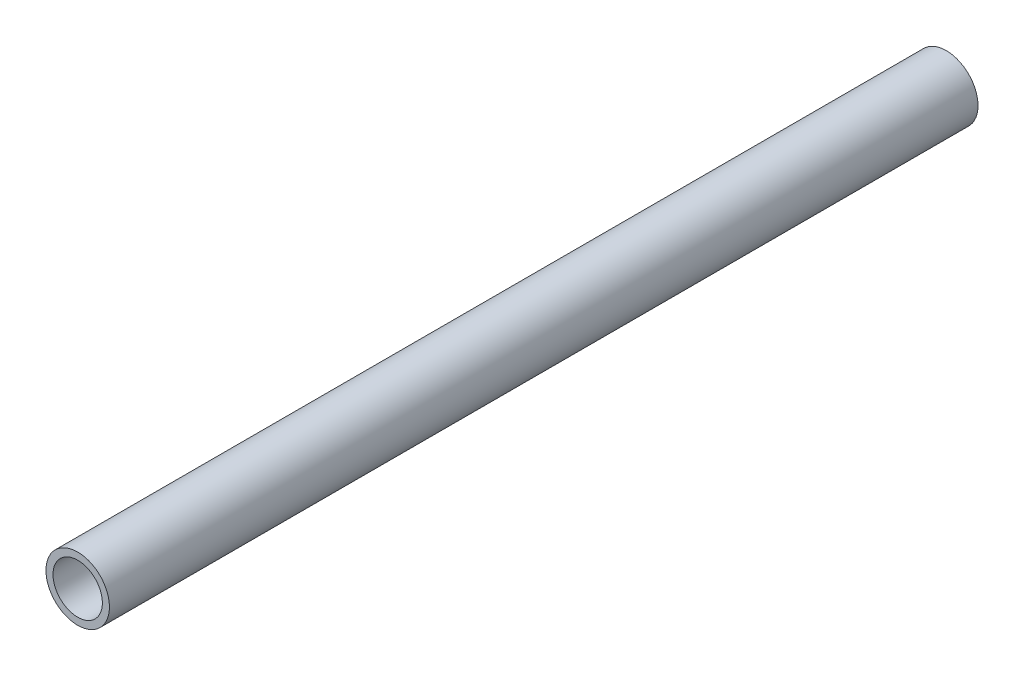
SolidWorks part; units mm, degrees
ref_plane "Front Plane" through (0, 0, 0) normal (0, 0, 1) x (1, 0, 0)
ref_plane "Top Plane" through (0, 0, 0) normal (0, 1, 0) x (1, 0, 0)
ref_plane "Right Plane" through (0, 0, 0) normal (1, 0, 0) x (0, 0, -1)
sketch "Sketch1" plane through (0, 0, 0) normal (0, 0, 1) x (1, 0, 0)
  circle A0 centre (0, 0) radius 9
  circle A1 centre (0, 0) radius 7
  dimension "D1" = 14
  dimension "D2" = 18
extrude "Boss-Extrude1" add sketch "Sketch1" along normal blind 246.188
